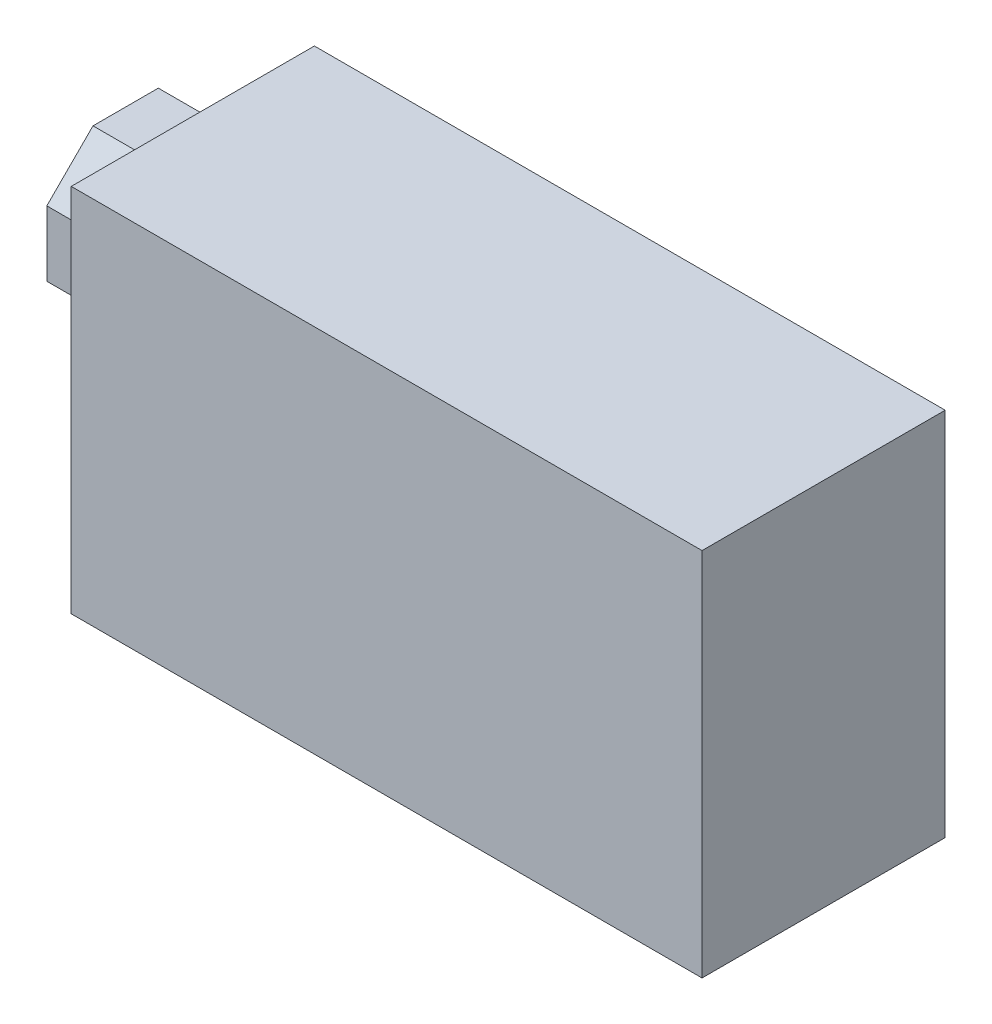
SolidWorks part; units mm, degrees
ref_plane "Front Plane" through (0, 0, 0) normal (0, 0, 1) x (1, 0, 0)
ref_plane "Top Plane" through (0, 0, 0) normal (0, 1, 0) x (1, 0, 0)
ref_plane "Right Plane" through (0, 0, 0) normal (1, 0, 0) x (0, 0, -1)
sketch "Sketch1" plane through (0, 0, 0) normal (0, 0, 1) x (1, 0, 0)
  line L1 (0, 0) -> (44.15, 0)
  line L2 (0, 0) -> (0, 25.908)
  line L3 (0, 25.908) -> (44.15, 25.908)
  line L4 (44.15, 0) -> (44.15, 25.908)
  dimension "D1" = 44.15
  dimension "D2" = 25.908
extrude "Boss-Extrude1" add sketch "Sketch1" along normal blind 17.018
sketch "Sketch2" plane through (0, 0, 0) normal (-1, 0, 0) x (0, 0, 1)
  line L0 (17.018, 25.908) -> (0, 25.908) construction
  line L2 (14.0279, 20.8834) -> (10.795, 24.1163)
  line L3 (10.795, 24.1163) -> (6.223, 24.1163)
  line L4 (6.223, 24.1163) -> (2.9901, 20.8834)
  line L5 (2.9901, 20.8834) -> (2.9901, 16.3114)
  line L6 (2.9901, 16.3114) -> (6.223, 13.0785)
  line L7 (6.223, 13.0785) -> (10.795, 13.0785)
  line L8 (10.795, 13.0785) -> (14.0279, 16.3114)
  line L9 (14.0279, 16.3114) -> (14.0279, 20.8834)
  circle A0 centre (8.509, 6.6027) radius 3.556
  circle A2 centre (8.509, 18.5974) radius 5.5189 construction
  point P3 (8.509, 6.6027)
  point P6 (8.509, 25.908)
  dimension "D1" = 4.572
  dimension "D2" = 7.112
extrude "Boss-Extrude2" add sketch "Sketch2" along normal blind 4.7
sketch "Sketch3" plane through (-4.7, 0, 0) normal (-1, 0, 0) x (0, 0, 1)
  line L1 (12.5689, 20.3763) -> (10.1293, 22.7291)
  line L2 (10.1293, 22.7291) -> (6.7406, 22.6678)
  line L3 (6.7406, 22.6678) -> (4.3878, 20.2282)
  line L4 (4.3878, 20.2282) -> (4.4491, 16.8395)
  line L5 (4.4491, 16.8395) -> (6.8887, 14.4867)
  line L6 (6.8887, 14.4867) -> (10.2774, 14.5481)
  line L7 (10.2774, 14.5481) -> (12.6302, 16.9876)
  line L8 (12.6302, 16.9876) -> (12.5689, 20.3763)
  circle A0 centre (8.509, 6.6027) radius 2.4386
  circle A1 centre (8.509, 18.6079) radius 4.0912 construction
extrude "Cut-Extrude1" cut sketch "Sketch3" against normal blind 3.81
